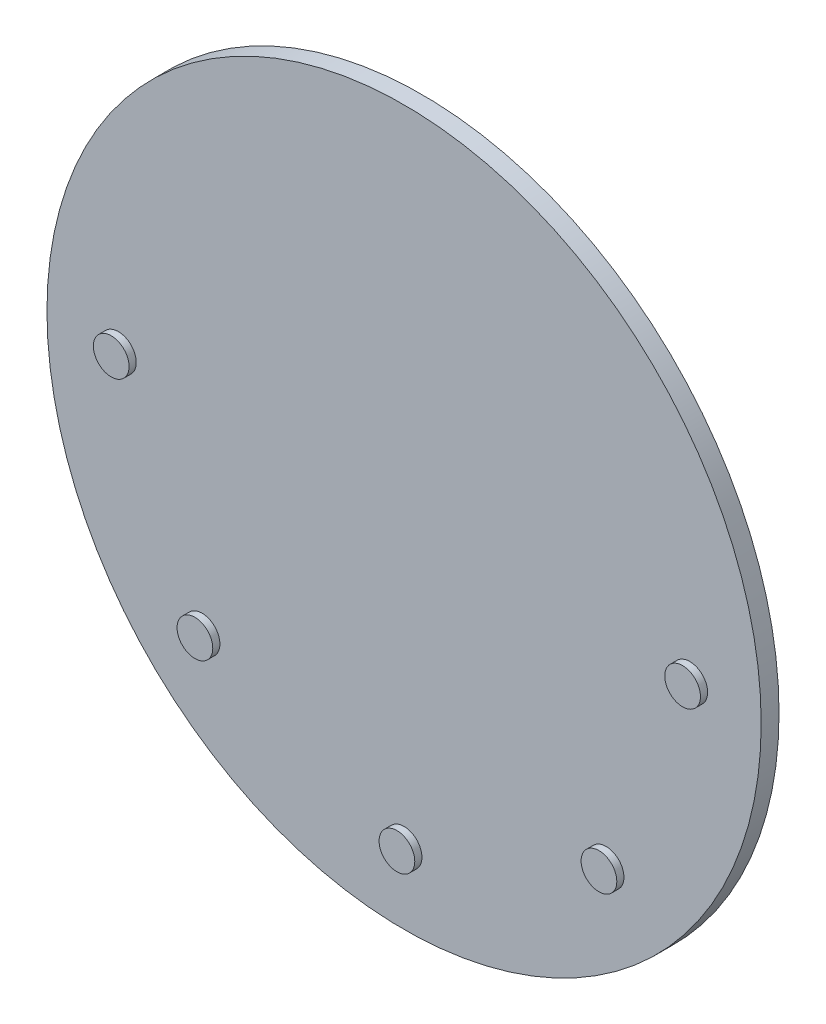
SolidWorks part; units mm, degrees
ref_plane "Спереди" through (0, 0, 0) normal (0, 0, 1) x (1, 0, 0)
ref_plane "Сверху" through (0, 0, 0) normal (0, 1, 0) x (1, 0, 0)
ref_plane "Справа" through (0, 0, 0) normal (1, 0, 0) x (0, 0, -1)
sketch "Эскиз1" plane through (0, 0, 0) normal (0, 0, 1) x (1, 0, 0)
  circle A0 centre (0, 0) radius 100
  dimension "D1" = 200
extrude "Бобышка-Вытянуть1" add sketch "Эскиз1" along normal blind 5
sketch "Эскиз2" plane through (0, 0, 5) normal (0, 0, 1) x (1, 0, 0)
  line L0 (-100, 0) -> (100, 0) construction
  line L1 (0, 0) -> (0, -100) construction
  line L2 (0, 0) -> (-70.7107, -70.7107) construction
  line L3 (70.7107, -70.7107) -> (0, 0) construction
  circle A0 centre (0, 0) radius 100 construction
  circle A1 centre (-80, 0) radius 5
  circle A2 centre (-56.5685, -56.5685) radius 5
  circle A3 centre (0, -80) radius 5
  circle A4 centre (56.5685, -56.5685) radius 5
  circle A5 centre (80, 0) radius 5
  point P20 (0, 0)
  dimension "D1" = 90
  dimension "D3" = 80
  dimension "D4" = 10
  dimension "D5" = 80
  dimension "D2" = 45
  dimension "D6" = 80
  dimension "D7" = 80
  dimension "D8" = 80
extrude "Бобышка-Вытянуть2" add sketch "Эскиз2" along normal blind 2 and the other way blind 7
